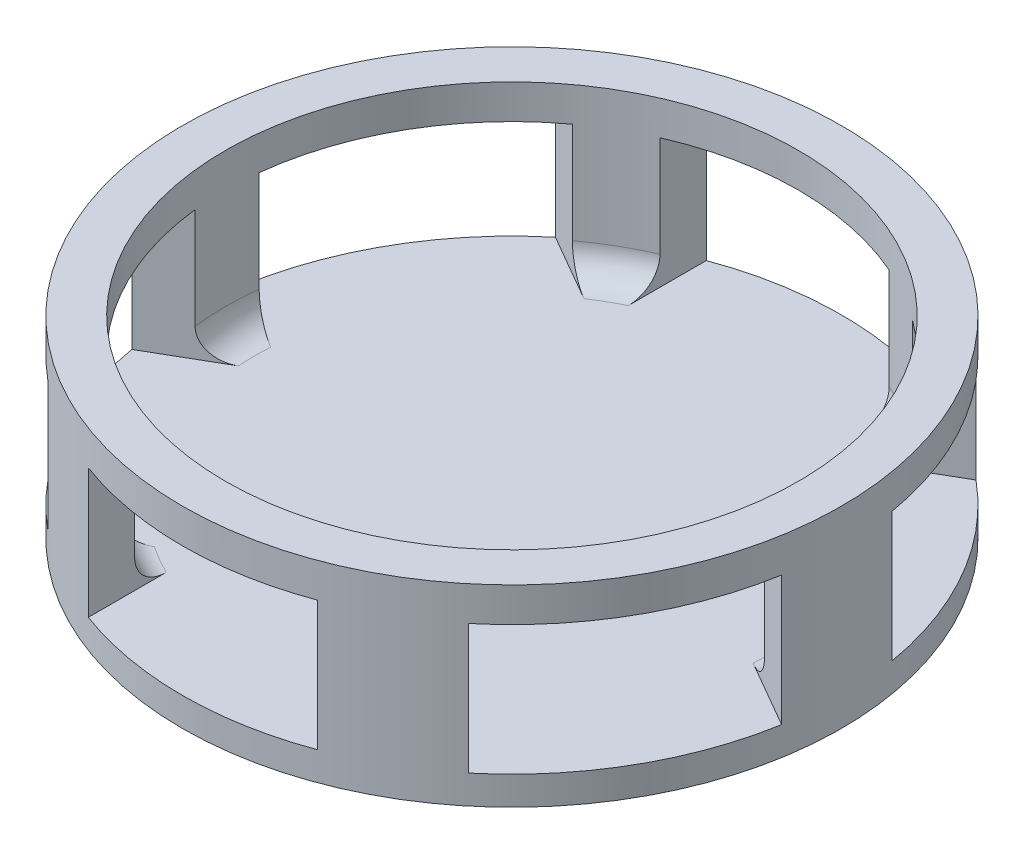
SolidWorks part; units mm, degrees
ref_plane "Front Plane" through (0, 0, 0) normal (0, 0, 1) x (1, 0, 0)
ref_plane "Top Plane" through (0, 0, 0) normal (0, 1, 0) x (1, 0, 0)
ref_plane "Right Plane" through (0, 0, 0) normal (1, 0, 0) x (0, 0, -1)
sketch "Sketch1" plane through (0, 0, 0) normal (0, 1, 0) x (1, 0, 0)
  circle A0 centre (0, 0) radius 57.5
  dimension "D1" = 115
extrude "Boss-Extrude1" add sketch "Sketch1" along normal blind 33.6
sketch "Sketch2" plane through (0, 33.6, 0) normal (0, 1, 0) x (1, 0, 0)
  circle A0 centre (0, 0) radius 50
  dimension "D1" = 100
extrude "Cut-Extrude1" cut sketch "Sketch2" against normal blind 28.6
fillet "Fillet1" radius 5 1 edges at (0, 5, 50)
sketch "Sketch3" plane through (0, 0, 0) normal (0, 0, 1) x (1, 0, 0)
  line L0 (-20, 5) -> (20, 5)
  line L2 (20, 5) -> (20, 27.6)
  line L3 (20, 27.6) -> (-20, 27.6)
  line L4 (-20, 27.6) -> (-20, 5)
  line L5 (50, 33.6) -> (-50, 33.6) construction
  line L6 (0, 58.7725) -> (0, -12.4276) construction
  line L7 (-57.5, 0) -> (57.5, 0) construction
  point P11 (20.0978, 0)
  dimension "D1" = 40
  dimension "D2" = 6
  dimension "D3" = 5
extrude "Cut-Extrude2" cut sketch "Sketch3" against normal through all both and the other way through all
pattern_circular "CirPattern1" count 3 over 360 about axis through (0, 0, 0) along (0, 1, 0) of "Cut-Extrude2"
